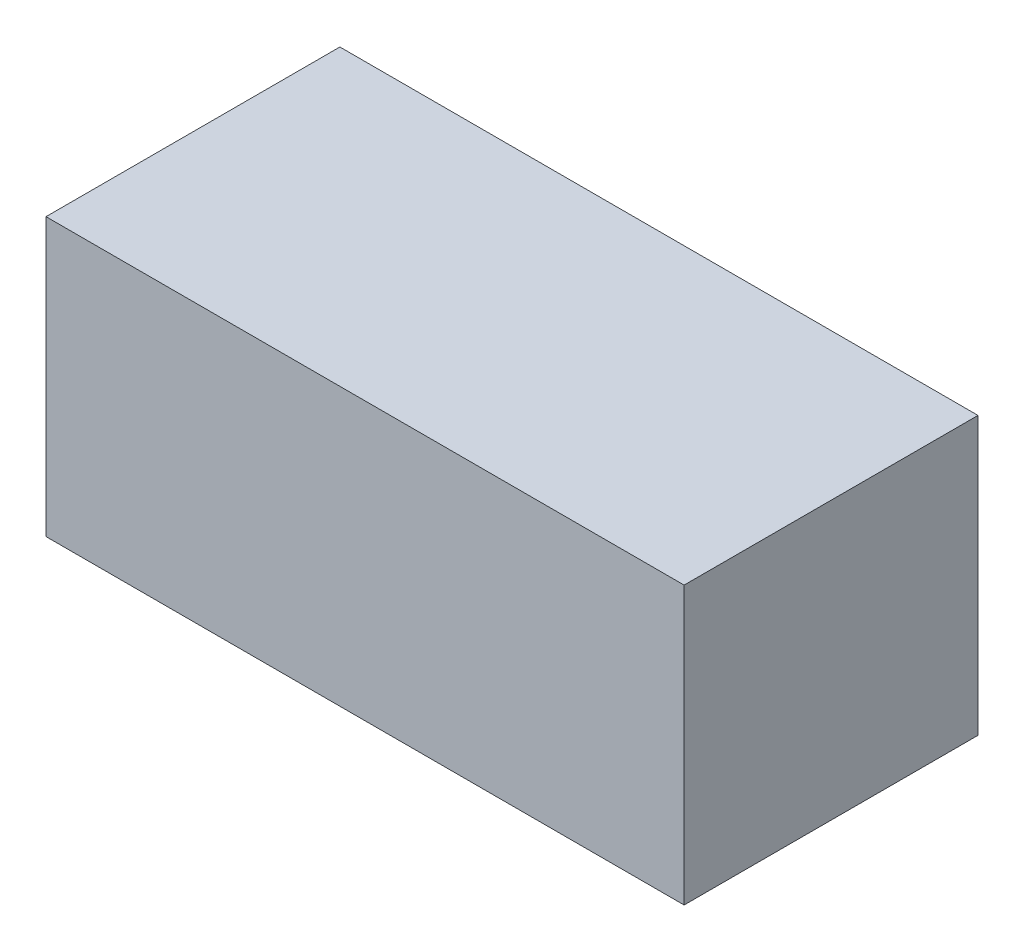
SolidWorks part; units mm, degrees
ref_plane "Front Plane" through (0, 0, 0) normal (0, 0, 1) x (1, 0, 0)
ref_plane "Top Plane" through (0, 0, 0) normal (0, 1, 0) x (1, 0, 0)
ref_plane "Right Plane" through (0, 0, 0) normal (1, 0, 0) x (0, 0, -1)
sketch "Sketch1" plane through (0, 0, 0) normal (0, 1, 0) x (1, 0, 0)
  line L1 (-38, -17.5) -> (38, -17.5)
  line L2 (-38, -17.5) -> (-38, 17.5)
  line L3 (-38, 17.5) -> (38, 17.5)
  line L4 (38, -17.5) -> (38, 17.5)
  line L5 (-38, -17.5) -> (38, 17.5) construction
  line L6 (-38, 17.5) -> (38, -17.5) construction
  point P0 (0, 0)
  dimension "D1" = 76
  dimension "D2" = 35
extrude "Boss-Extrude1" add sketch "Sketch1" along normal blind 33
